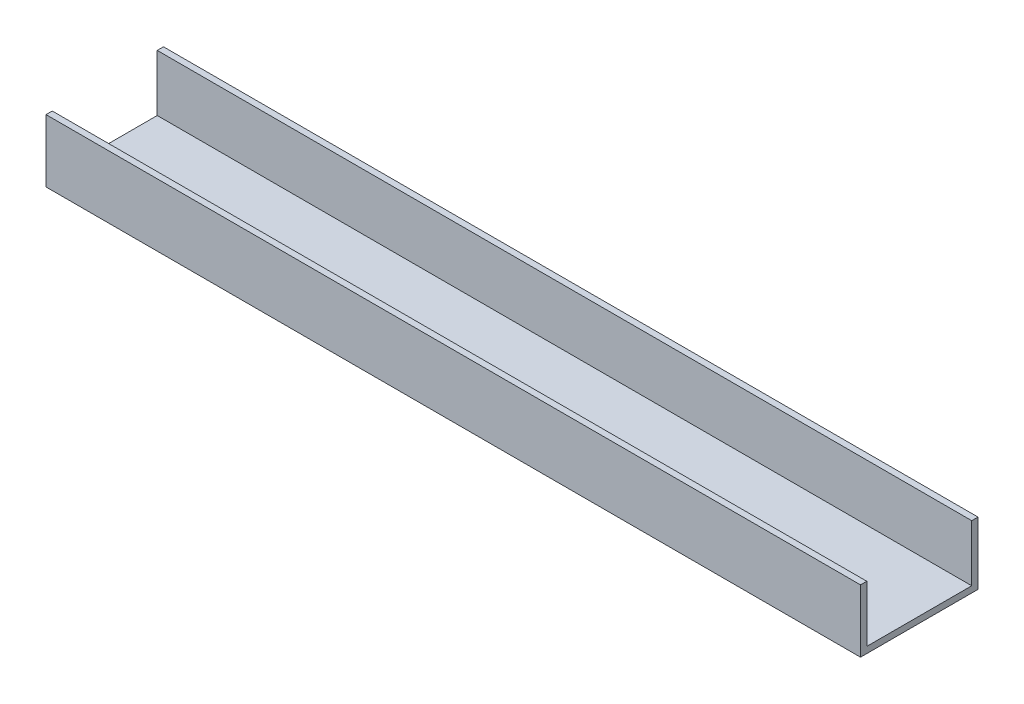
SolidWorks part; units mm, degrees
ref_plane "정면" through (0, 0, 0) normal (0, 0, 1) x (1, 0, 0)
ref_plane "윗면" through (0, 0, 0) normal (0, 1, 0) x (1, 0, 0)
ref_plane "우측면" through (0, 0, 0) normal (1, 0, 0) x (0, 0, -1)
sketch "스케치1" plane through (0, 0, 0) normal (0, 1, 0) x (1, 0, 0)
  line L1 (0, 0) -> (520, 0)
  line L2 (0, 0) -> (0, 75)
  line L3 (0, 75) -> (520, 75)
  line L4 (520, 0) -> (520, 75)
  dimension "D1" = 520
  dimension "D2" = 75
extrude "보스-돌출1" add sketch "스케치1" along normal blind 4
sketch "스케치2" plane through (0, 4, 0) normal (0, 1, 0) x (1, 0, 0)
  line L0 (520, 0) -> (520, 75) construction
  line L1 (0, 0) -> (520, 0)
  line L2 (0, 0) -> (0, 4)
  line L3 (0, 4) -> (520, 4)
  line L4 (520, 0) -> (520, 4)
  line L5 (0, 75) -> (0, 0) construction
  line L6 (520, 75) -> (0, 75)
  line L7 (520, 75) -> (520, 71)
  line L8 (520, 71) -> (0, 71)
  line L9 (0, 75) -> (0, 71)
  dimension "D1" = 4
  dimension "D2" = 4
extrude "보스-돌출2" add sketch "스케치2" along normal blind 36
